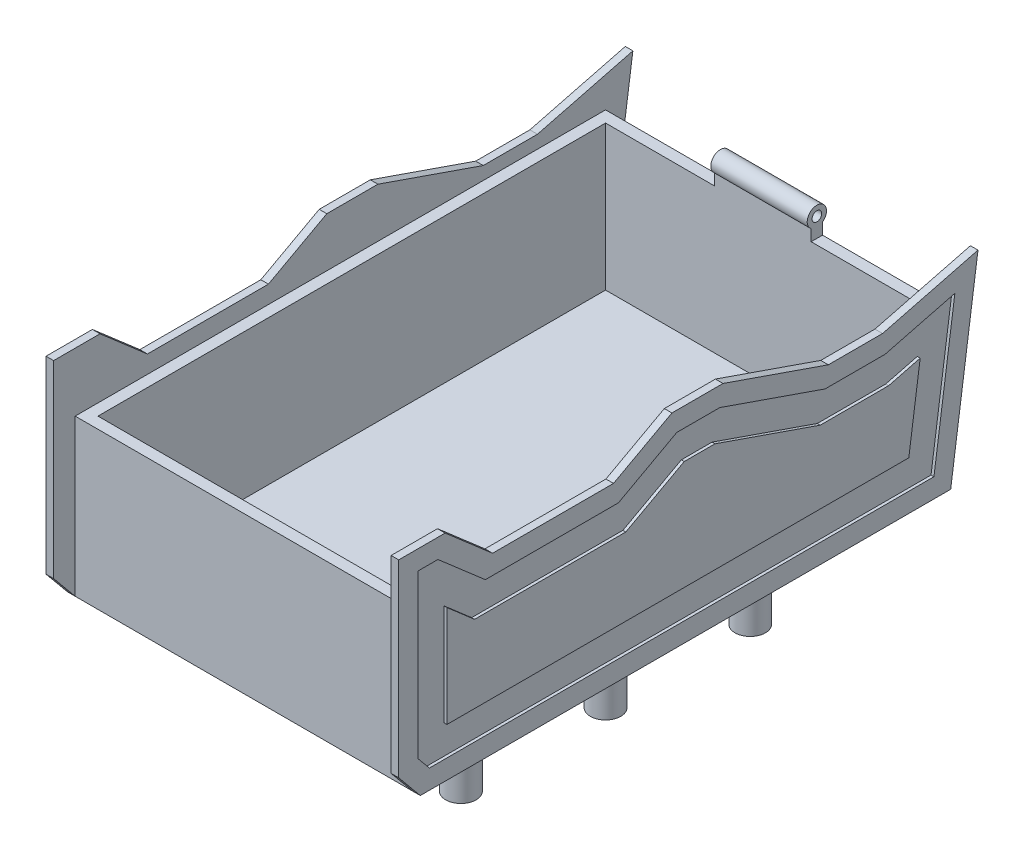
SolidWorks part; units mm, degrees
ref_plane "Front Plane" through (0, 0, 0) normal (0, 0, 1) x (1, 0, 0)
ref_plane "Top Plane" through (0, 0, 0) normal (0, 1, 0) x (1, 0, 0)
ref_plane "Right Plane" through (0, 0, 0) normal (1, 0, 0) x (0, 0, -1)
sketch "Sketch2" plane through (0, 0, 0) normal (0, 1, 0) x (1, 0, 0)
  line L1 (-44.45, 69.85) -> (44.45, 69.85)
  line L2 (-44.45, 69.85) -> (-44.45, -69.85)
  line L3 (-44.45, -69.85) -> (44.45, -69.85)
  line L4 (44.45, 69.85) -> (44.45, -69.85)
  line L5 (-44.45, 69.85) -> (44.45, -69.85) construction
  line L6 (-44.45, -69.85) -> (44.45, 69.85) construction
  point P0 (0, 0)
  dimension "D1" = 139.7
  dimension "D2" = 88.9
extrude "Boss-Extrude1" add sketch "Sketch2" along normal blind 3
sketch "Sketch3" plane through (0, 0, 0) normal (0, -1, 0) x (1, 0, 0)
  line L0 (0, -69.85) -> (0, 69.85) construction
  line L1 (44.45, -69.85) -> (-44.45, -69.85) construction
  line L2 (-44.45, 69.85) -> (44.45, 69.85) construction
  line L3 (-44.45, 0) -> (44.45, 0) construction
  line L4 (-44.45, -69.85) -> (-44.45, 69.85) construction
  line L5 (44.45, 69.85) -> (44.45, -69.85) construction
  circle A0 centre (-25.4, 0) radius 4
  circle A1 centre (-25.4, 38.1) radius 4
  circle A2 centre (-25.4, -38.1) radius 4
  circle A3 centre (25.4, -38.1) radius 4
  circle A4 centre (25.4, 38.1) radius 4
  circle A5 centre (25.4, 0) radius 4
  point P18 (0, 0)
  dimension "D3" = 8
  dimension "D1" = 38.1
  dimension "D2" = 38.1
  dimension "D4" = 25.4
extrude "Boss-Extrude2" add sketch "Sketch3" along normal blind 25.4
sketch "Sketch4" plane through (0, 3, 0) normal (0, 1, 0) x (1, 0, 0)
  line L0 (41.45, -66.85) -> (41.45, 66.85)
  line L1 (41.45, 66.85) -> (-41.45, 66.85)
  line L2 (-41.45, 66.85) -> (-41.45, -66.85)
  line L3 (-41.45, -66.85) -> (41.45, -66.85)
  line L4 (44.45, -69.85) -> (44.45, 69.85)
  line L5 (44.45, 69.85) -> (-44.45, 69.85)
  line L6 (-44.45, 69.85) -> (-44.45, -69.85)
  line L7 (-44.45, -69.85) -> (44.45, -69.85)
  line L8 (44.45, -69.85) -> (44.45, 69.85)
  line L9 (44.45, 69.85) -> (-44.45, 69.85)
  line L10 (-44.45, 69.85) -> (-44.45, -69.85)
  line L11 (-44.45, -69.85) -> (44.45, -69.85)
  dimension "D1" = 0
  dimension "D2" = 3
extrude "Boss-Extrude3" add sketch "Sketch4" along normal blind 38.1
sketch "Sketch5" plane through (-44.45, 0, 0) normal (-1, 0, 0) x (0, 0, 1)
  line L0 (-69.85, 0) -> (-77.0439, 50.9726)
  line L1 (-77.0439, 50.9726) -> (-51.9119, 44.5179)
  line L2 (-51.9119, 44.5179) -> (-37.6293, 44.5179)
  line L3 (-37.6293, 44.5179) -> (-9.888, 54.1313)
  line L4 (-9.888, 54.1313) -> (3.5707, 54.1313)
  line L5 (3.5707, 54.1313) -> (18.952, 45.7539)
  line L6 (18.952, 45.7539) -> (50.8132, 45.7539)
  line L7 (50.8132, 45.7539) -> (63.3106, 56.6033)
  line L8 (63.3106, 56.6033) -> (75.5332, 56.6033)
  line L9 (75.5332, 56.6033) -> (75.5332, 6.8887)
  line L10 (75.5332, 6.8887) -> (69.85, 0)
  line L11 (69.85, 0) -> (-69.85, 0)
extrude "Boss-Extrude4" add sketch "Sketch5" along normal blind 2
mirror "Mirror1" about plane through (0, 0, 0) normal (1, 0, 0) of "Boss-Extrude4"
sketch "Sketch6" plane through (0, 0, 0) normal (1, 0, 0) x (0, 0, -1)
  line L0 (69.85, 41.1) -> (69.85, 44.1)
  line L2 (66.85, 44.1) -> (66.85, 41.1)
  line L3 (66.85, 41.1) -> (69.85, 41.1)
  arc A0 (69.85, 44.1) -> (66.85, 44.1) centre (68.35, 46.1498) ccw
  circle A1 centre (68.35, 46.1498) radius 1.27
  dimension "D2" = 2.54
  dimension "D3" = 2.54
  dimension "D1" = 3
extrude "Boss-Extrude5" add sketch "Sketch6" along normal mid plane 25.4
sketch "Sketch8" plane through (46.45, 0, 0) normal (1, 0, 0) x (0, 0, -1)
  line L12 (-62.8332, 12.7) -> (58.8165, 12.7)
  line L13 (58.8165, 12.7) -> (61.8155, 33.9493)
  line L14 (61.8155, 33.9493) -> (53.5167, 31.8179)
  line L15 (53.5167, 31.8179) -> (35.4911, 31.8179)
  line L16 (35.4911, 31.8179) -> (7.7499, 41.4313)
  line L17 (7.7499, 41.4313) -> (-0.3365, 41.4313)
  line L18 (-0.3365, 41.4313) -> (-15.7178, 33.0539)
  line L19 (-15.7178, 33.0539) -> (-55.5568, 33.0539)
  line L20 (-55.5568, 33.0539) -> (-62.8332, 39.3708)
  line L21 (-62.8332, 39.3708) -> (-62.8332, 39.3708)
  line L22 (-62.8332, 39.3708) -> (-62.8332, 12.7)
  line L23 (-62.8332, 12.7) -> (-62.8332, 12.7)
  line L24 (-67.4554, 5.08) -> (65.4366, 5.08)
  line L25 (65.4366, 5.08) -> (70.9525, 44.1633)
  line L26 (70.9525, 44.1633) -> (52.5538, 39.4379)
  line L27 (52.5538, 39.4379) -> (36.774, 39.4379)
  line L28 (36.774, 39.4379) -> (9.0327, 49.0513)
  line L29 (9.0327, 49.0513) -> (-2.277, 49.0513)
  line L30 (-2.277, 49.0513) -> (-17.6583, 40.6739)
  line L31 (-17.6583, 40.6739) -> (-52.7107, 40.6739)
  line L32 (-52.7107, 40.6739) -> (-65.208, 51.5233)
  line L33 (-65.208, 51.5233) -> (-70.4532, 51.5233)
  line L34 (-70.4532, 51.5233) -> (-70.4532, 8.7137)
  line L35 (-70.4532, 8.7137) -> (-67.4554, 5.08)
  line L36 (-67.4554, 5.08) -> (65.4366, 5.08)
  line L37 (65.4366, 5.08) -> (70.9525, 44.1633)
  line L38 (70.9525, 44.1633) -> (52.5538, 39.4379)
  line L39 (52.5538, 39.4379) -> (36.774, 39.4379)
  line L40 (36.774, 39.4379) -> (9.0327, 49.0513)
  line L41 (9.0327, 49.0513) -> (-2.277, 49.0513)
  line L42 (-2.277, 49.0513) -> (-17.6583, 40.6739)
  line L43 (-17.6583, 40.6739) -> (-52.7107, 40.6739)
  line L44 (-52.7107, 40.6739) -> (-65.208, 51.5233)
  line L45 (-65.208, 51.5233) -> (-70.4532, 51.5233)
  line L46 (-70.4532, 51.5233) -> (-70.4532, 8.7137)
  line L47 (-70.4532, 8.7137) -> (-67.4554, 5.08)
  dimension "D1" = 5.08
  dimension "D2" = 7.62
extrude "Cut-Extrude1" cut sketch "Sketch8" against normal blind 0.762
mirror "Mirror2" about plane through (0, 0, 0) normal (1, 0, 0) of "Cut-Extrude1"
sketch "Sketch9" plane through (0, 0, -69.85) normal (0, 0, -1) x (-1, 0, 0)
  line L0 (0, 10.8866) -> (0, 44.1) construction
  line L1 (-12.7, 44.1) -> (12.7, 44.1) construction
  line L2 (-15.3356, 29.1637) -> (-6.1809, 39.2053)
  line L3 (-6.1809, 39.2053) -> (-12.6508, 32.1086)
  line L4 (-6.1809, 39.2053) -> (-3.3384, 32.1086)
  line L5 (-3.3384, 32.1086) -> (-0.7797, 29.7759)
  line L6 (-0.7797, 29.7759) -> (-4.7596, 20.1919)
  line L7 (-4.7596, 20.1919) -> (-12.6508, 13.9324)
  line L8 (-12.6508, 13.9324) -> (-2.059, 11.7416)
  line L9 (-2.059, 11.7416) -> (0, 10.8866)
  line L11 (15.3356, 29.1637) -> (6.1809, 39.2053)
  line L12 (2.059, 11.7416) -> (0, 10.8866)
  line L13 (12.6508, 13.9324) -> (2.059, 11.7416)
  line L14 (4.7596, 20.1919) -> (12.6508, 13.9324)
  line L15 (0.7797, 29.7759) -> (4.7596, 20.1919)
  line L16 (3.3384, 32.1086) -> (0.7797, 29.7759)
  line L17 (6.1809, 39.2053) -> (3.3384, 32.1086)
  spline S0 degree 3 poles (0, 2.2323) (-3.1917, 2.469) (-10.5768, 3.0167) (-19.6263, 8.2347) (-29.624, 1.4839) (-40.1592, 15.5561) (-37.2486, 4.0124) (-44.2453, 41.6089) (-29.1938, 38.0422) (-20.009, 33.4244) (-15.3356, 29.1637) knots 0 0 0 0 0.123775 0.286397 0.321357 0.473376 0.634369 0.669519 0.824877 1 1 1 1
  spline S1 degree 3 poles (0, 2.2323) (3.1917, 2.469) (10.5768, 3.0167) (19.6263, 8.2347) (29.624, 1.4839) (40.1592, 15.5561) (37.2486, 4.0124) (44.2453, 41.6089) (29.1938, 38.0422) (20.009, 33.4244) (15.3356, 29.1637) knots 0 0 0 0 0.123775 0.286397 0.321357 0.473376 0.634369 0.669519 0.824877 1 1 1 1
  point P19 (0, 0)
  point P20 (0, 0)
  point P33 (0, 0)
  point P34 (0, 2.2323)
extrude "Cut-Extrude6" cut sketch "Sketch9" against normal blind 0.762 contours S0 S1 L11 L17 L16 L15 L14 L13 L12 L9 L8 L7 L6 L5 L4 L2
